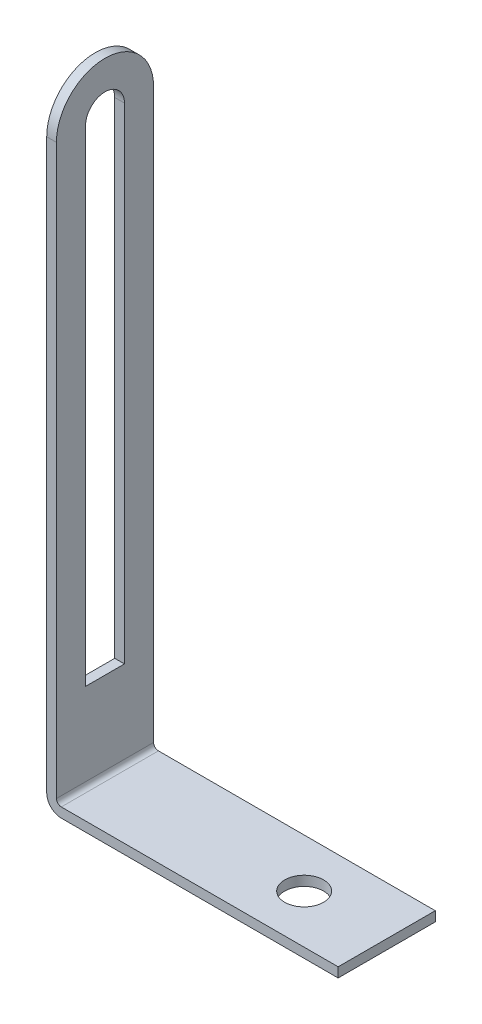
SolidWorks part; units mm, degrees
material "Messing mit hohem Bleigehalt, UNS C34200"
ref_plane "Ebene vorne" through (0, 0, 0) normal (0, 0, 1) x (1, 0, 0)
ref_plane "Ebene oben" through (0, 0, 0) normal (0, 1, 0) x (1, 0, 0)
ref_plane "Ebene rechts" through (0, 0, 0) normal (1, 0, 0) x (0, 0, -1)
sketch "Skizze1" plane through (0, 0, 0) normal (1, 0, 0) x (0, 0, -1)
  line L0 (-5, -25) -> (-5, -33.5)
  line L1 (-5, 25) -> (5, 25) construction
  line L2 (-5, 25) -> (-5, -25)
  line L3 (-5, -25) -> (5, -25) construction
  line L4 (5, 25) -> (5, -25)
  line L5 (-5, 25) -> (5, -25) construction
  line L6 (-5, -25) -> (5, 25) construction
  line L7 (-2, 25) -> (2, 25) construction
  line L8 (-2, 25) -> (-2, -25)
  line L9 (-2, -25) -> (2, -25)
  line L10 (2, 25) -> (2, -25)
  line L11 (-2, 25) -> (2, -25) construction
  line L12 (-2, -25) -> (2, 25) construction
  line L13 (-5, -33.5) -> (5, -33.5)
  line L14 (5, -33.5) -> (5, -25)
  arc A0 (-2, 25) -> (2, 25) centre (0, 25) cw
  arc A1 (-5, 25) -> (5, 25) centre (0, 25) cw
  point P0 (0, 0)
  point P6 (0, 0)
  dimension "D1" = 10
  dimension "D2" = 4
  dimension "D3" = 50
  dimension "D4" = 8.5
extrude "Aufsatz-Linear austragen1" add sketch "Skizze1" along normal blind 1
sketch "Skizze2" plane through (0, 0, 5) normal (0, 0, 1) x (1, 0, 0)
  line L1 (0, -33.5) -> (1.5, -33.5) construction
  line L2 (0, -33.5) -> (0, -35) construction
  line L3 (0, -35) -> (1.5, -35) construction
  line L4 (1.5, -33.5) -> (1.5, -35) construction
  line L5 (0, -33.5) -> (1.5, -35) construction
  line L6 (0, -35) -> (1.5, -33.5) construction
  line L7 (1.5, -34) -> (30, -34)
  line L8 (1.5, -34) -> (1.5, -35) construction
  line L9 (1.5, -35) -> (30, -35)
  line L10 (30, -34) -> (30, -35)
  line L11 (1.5, -34) -> (30, -35) construction
  line L12 (1.5, -35) -> (30, -34) construction
  line L16 (0, 25) -> (0, -33.5)
  line L17 (0, -33.5) -> (1, -33.5)
  line L18 (1, -33.5) -> (1, 25)
  line L19 (1, 25) -> (0, 25)
  line L21 (0, -33.5) -> (1, -33.5)
  arc A0 (1, -33.5) -> (1.5, -34) centre (1.5, -33.5) ccw
  arc A1 (0, -33.5) -> (1.5, -35) centre (1.5, -33.5) ccw
  point P4 (0.75, -34.25)
  point P12 (15.75, -34.5)
  dimension "D1" = 1.5
  dimension "D2" = 28.5
  dimension "D3" = 0
extrude "Aufsatz-Linear austragen2" add sketch "Skizze2" against normal up to surface (10 mm away) up to face at (0.5, -4.25, -5)
sketch "Skizze3" plane through (0, -35, 0) normal (0, -1, 0) x (1, 0, 0)
  line L0 (30, 0) -> (0, 0) construction
  line L1 (30, -5) -> (30, 5) construction
  line L2 (0, 5) -> (0, -5) construction
  circle A0 centre (21.5, 0) radius 2
  dimension "D1" = 4
  dimension "D2" = 21.5
extrude "Schnitt-Linear austragen1" cut sketch "Skizze3" against normal through all
